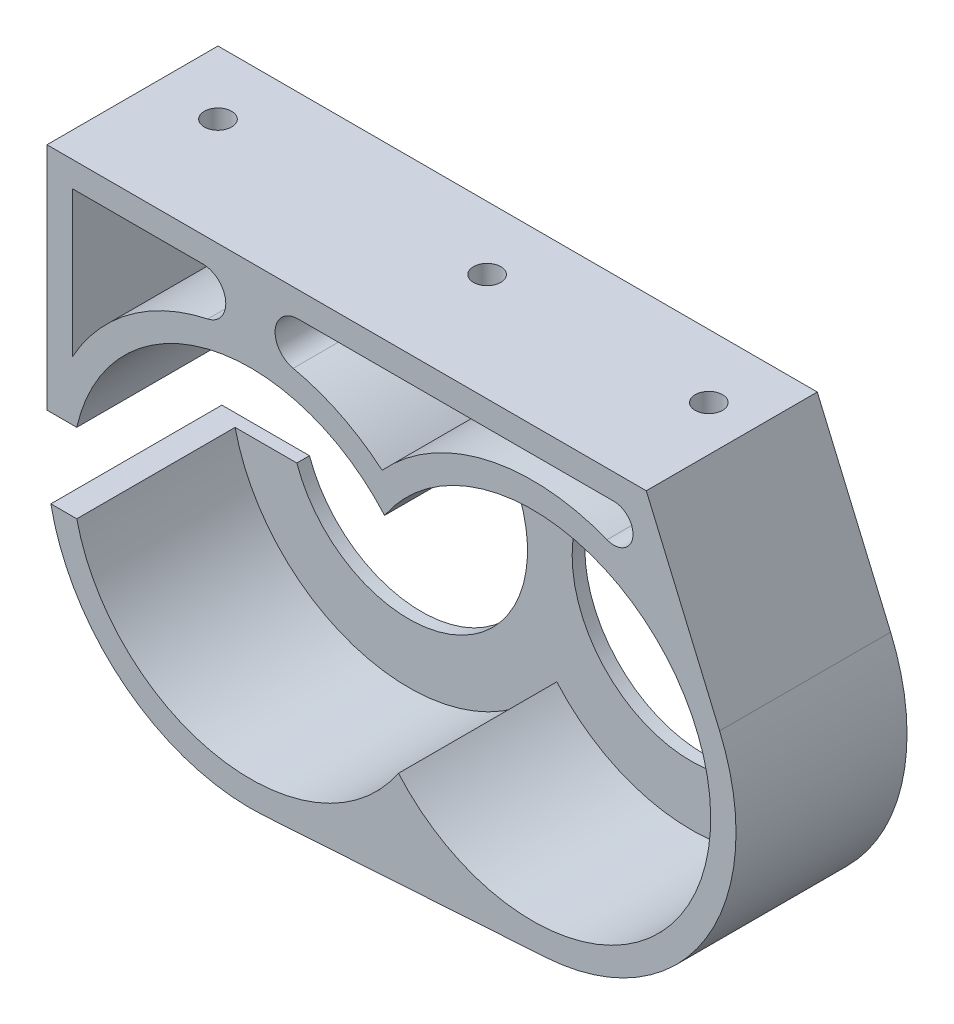
SolidWorks part; units mm, degrees
ref_plane "Front Plane" through (0, 0, 0) normal (0, 0, 1) x (1, 0, 0)
ref_plane "Top Plane" through (0, 0, 0) normal (0, 1, 0) x (1, 0, 0)
ref_plane "Right Plane" through (0, 0, 0) normal (1, 0, 0) x (0, 0, -1)
sketch "Sketch1" plane through (0, 0, 0) normal (0, 0, 1) x (1, 0, 0)
  line L0 (37.2816, -23.3608) -> (1.6456, -25.6473)
  line L1 (59.262, 12.4009) -> (50, 34.036)
  line L3 (-25.7, 34.036) -> (-25.7, 0)
  line L4 (-25.7, 34.036) -> (50, 34.036)
  arc A0 (16.9413, 14.8068) -> (18.6947, -12.5203) centre (0, 0) ccw
  arc A1 (18.6947, -12.5203) -> (16.9413, 14.8068) centre (35.636, 2.2865) ccw
  arc A2 (37.2816, -23.3608) -> (59.262, 12.4009) centre (35.636, 2.2865) ccw
  arc A3 (-25.7, 0) -> (1.6456, -25.6473) centre (0, 0) ccw
  circle A4 centre (35.636, 2.2865) radius 25.7 construction
  circle A5 centre (0, 0) radius 25.7 construction
  circle A6 centre (0, 0) radius 22.5 construction
  circle A7 centre (35.636, 2.2865) radius 22.5 construction
  dimension "D1" = 45
  dimension "D2" = 3.2
extrude "Boss-Extrude1" add sketch "Sketch1" along normal blind 20
sketch "Sketch2" plane through (0, 0, 0) normal (0, 0, -1) x (-1, 0, 0)
  line L4 (25.7, 0) -> (25.7, 34.036)
  line L5 (25.7, 34.036) -> (-50, 34.036)
  line L6 (-50, 34.036) -> (-59.262, 12.4009)
  line L7 (-37.2816, -23.3608) -> (-1.6456, -25.6473)
  line L8 (25.7, 0) -> (25.7, 34.036)
  line L10 (-50, 34.036) -> (-59.262, 12.4009)
  line L11 (-37.2816, -23.3608) -> (-1.6456, -25.6473)
  line L12 (25.7, 34.036) -> (-50, 34.036)
  arc A2 (-59.262, 12.4009) -> (-37.2816, -23.3608) centre (-35.636, 2.2865) ccw
  arc A3 (-1.6456, -25.6473) -> (25.7, 0) centre (0, 0) ccw
  arc A4 (-59.262, 12.4009) -> (-37.2816, -23.3608) centre (-35.636, 2.2865) ccw
  arc A5 (-1.6456, -25.6473) -> (25.7, 0) centre (0, 0) ccw
  dimension "D1" = 0
extrude "Boss-Extrude2" add sketch "Sketch2" along normal blind 1.6
sketch "Sketch3" plane through (0, 0, 20) normal (0, 0, 1) x (1, 0, 0)
  line L0 (-6, 30.836) -> (-22.5, 30.836)
  line L1 (-6, 30.836) -> (-22.5, 30.836)
  line L5 (47.889, 30.836) -> (-22.5, 30.836)
  line L6 (45.9226, 30.836) -> (6, 30.836)
  line L8 (-22.5, 30.836) -> (-22.5, 0)
  line L9 (1.4407, -22.4538) -> (37.0767, -20.1673)
  line L10 (56.3203, 11.1415) -> (47.889, 30.836)
  line L12 (-22.5, 30.836) -> (-22.5, 12.4193)
  arc A0 (45.9226, 30.836) -> (45.044, 26.2026) centre (45.9226, 28.436) cw
  arc A1 (-6, 30.836) -> (-5.3942, 25.1275) centre (-6, 27.9496) cw
  arc A2 (6, 30.836) -> (5.3942, 25.1275) centre (6, 27.9496) ccw
  arc A3 (-5.3942, 25.1275) -> (-22.5, 12.4193) centre (0, 0) ccw
  arc A4 (-22.5, 0) -> (1.4407, -22.4538) centre (0, 0) ccw
  arc A5 (37.0767, -20.1673) -> (56.3203, 11.1415) centre (35.636, 2.2865) ccw
  arc A10 (19.0016, -17.304) -> (16.6344, 19.5905) centre (35.636, 2.2865) ccw
  arc A11 (16.6344, 19.5905) -> (19.0016, -17.304) centre (0, 0) ccw
  arc A12 (45.044, 26.2026) -> (16.6344, 19.5905) centre (35.636, 2.2865) ccw
  arc A13 (16.6344, 19.5905) -> (5.3942, 25.1275) centre (0, 0) ccw
  dimension "D3" = 2.4
  dimension "D4" = 12
  dimension "D1" = 3.2
  dimension "D2" = 3.2
extrude "Cut-Extrude1" cut sketch "Sketch3" against normal up to next contours A3 A1 L0 L12 | A13 A12 A0 L6 A2
sketch "Sketch4" plane through (0, 0, 20) normal (0, 0, 1) x (1, 0, 0)
  line L2 (37.0767, -20.1673) -> (1.4407, -22.4538)
  line L3 (24.6828, -20.9625) -> (13.8346, -21.6586)
  arc A4 (16.6344, 19.5905) -> (19.0016, -17.304) centre (0, 0) ccw
  arc A5 (19.0016, -17.304) -> (16.6344, 19.5905) centre (35.636, 2.2865) ccw
  arc A6 (13.8346, -21.6586) -> (19.0016, -17.304) centre (0, 0) ccw
  arc A7 (19.0016, -17.304) -> (24.6828, -20.9625) centre (35.636, 2.2865) ccw
  dimension "D1" = 3.2
  dimension "D2" = 3.2
extrude "Cut-Extrude2" [suppressed] cut sketch "Sketch4" against normal through all
sketch "Sketch5" plane through (0, 0, -1.6) normal (0, 0, -1) x (-1, 0, 0)
  line L0 (25.7, 5) -> (0, 5)
  line L1 (25.7, 0) -> (25.7, 34.036) construction
  line L2 (0, -5) -> (25.2089, -5)
  line L3 (25.7, 0) -> (25.7, 5)
  arc A0 (0, 5) -> (0, -5) centre (0, 0) ccw
  arc A1 (-1.6456, -25.6473) -> (25.7, 0) centre (0, 0) ccw construction
  arc A2 (25.2089, -5) -> (25.7, 0) centre (0, 0) ccw
  dimension "D1" = 5
extrude "Cut-Extrude3" cut sketch "Sketch5" against normal up to next
sketch "Sketch6" plane through (0, 0, -1.6) normal (0, 0, -1) x (-1, 0, 0)
  circle A0 centre (-35.636, 2.2865) radius 15
  arc A1 (-59.262, 12.4009) -> (-37.2816, -23.3608) centre (-35.636, 2.2865) ccw construction
  circle A2 centre (0, 0) radius 15
  dimension "D1" = 30
extrude "Cut-Extrude4" cut sketch "Sketch6" against normal up to next
hole_wizard "#8-32 Tapped Hole1" positions "Sketch7" profile "Sketch8" tap size "#8-32" standard "ANSI Inch"
sketch "Sketch7" plane through (0, 34.036, 0) normal (0, 1, 0) x (1, 0, 0)
  line L1 (-25.7, -20) -> (-25.7, 1.6) construction
  line L3 (50, -6.4) -> (-25.7, -6.4) construction
  line L4 (50, -20) -> (50, 1.6) construction
  line L6 (-25.7, 1.6) -> (50, 1.6) construction
  point P0 (16.3, -6.4)
  point P2 (-17.7, -6.4)
  point P14 (44.3, -6.4)
  dimension "D1" = 8
  dimension "D2" = 42
  dimension "D3" = 70
  dimension "D4" = 8
sketch "Sketch8" plane through (16.3, 34.036, 6.4) normal (1, 0, 0) x (0, 0, 1)
  line L0 (0, 0) -> (0, 3.2)
  line L1 (0, 3.2) -> (1.7272, 3.2)
  line L2 (1.7272, 3.2) -> (1.7272, 0)
  line L5 (1.7272, 0) -> (0, 0)
  line L11 (0, -6.35) -> (0, 107.95) construction
  dimension "Thread Major Dia." = 3.4544
  dimension "Thru Tap Drill Depth" = 3.2
